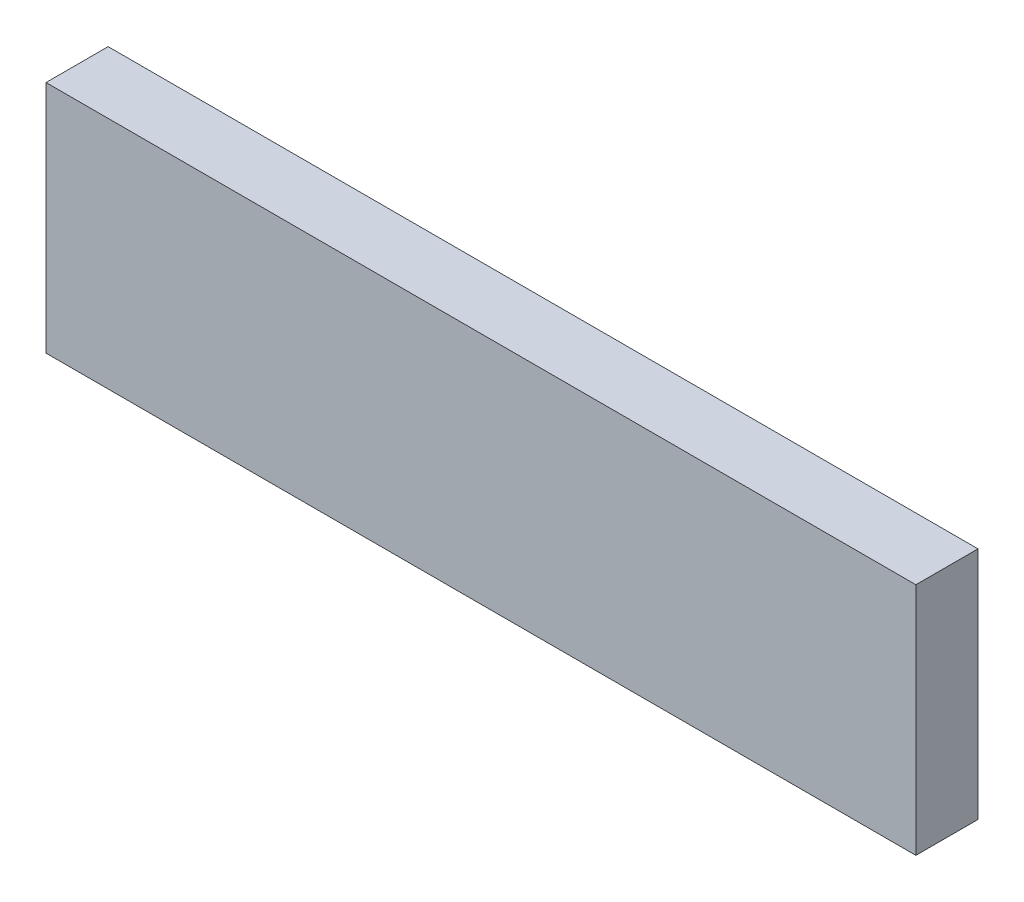
SolidWorks part; units mm, degrees
ref_plane "Alzado" through (0, 0, 0) normal (0, 0, 1) x (1, 0, 0)
ref_plane "Planta" through (0, 0, 0) normal (0, 1, 0) x (1, 0, 0)
ref_plane "Vista lateral" through (0, 0, 0) normal (1, 0, 0) x (0, 0, -1)
sketch "Croquis1" plane through (0, 0, 0) normal (0, 0, 1) x (1, 0, 0)
  line L1 (0, 0) -> (70, 0)
  line L2 (0, 0) -> (0, 18.8612)
  line L3 (0, 18.8612) -> (70, 18.8612)
  line L4 (70, 0) -> (70, 18.8612)
extrude "Saliente-Extruir1" add sketch "Croquis1" along normal blind 5
